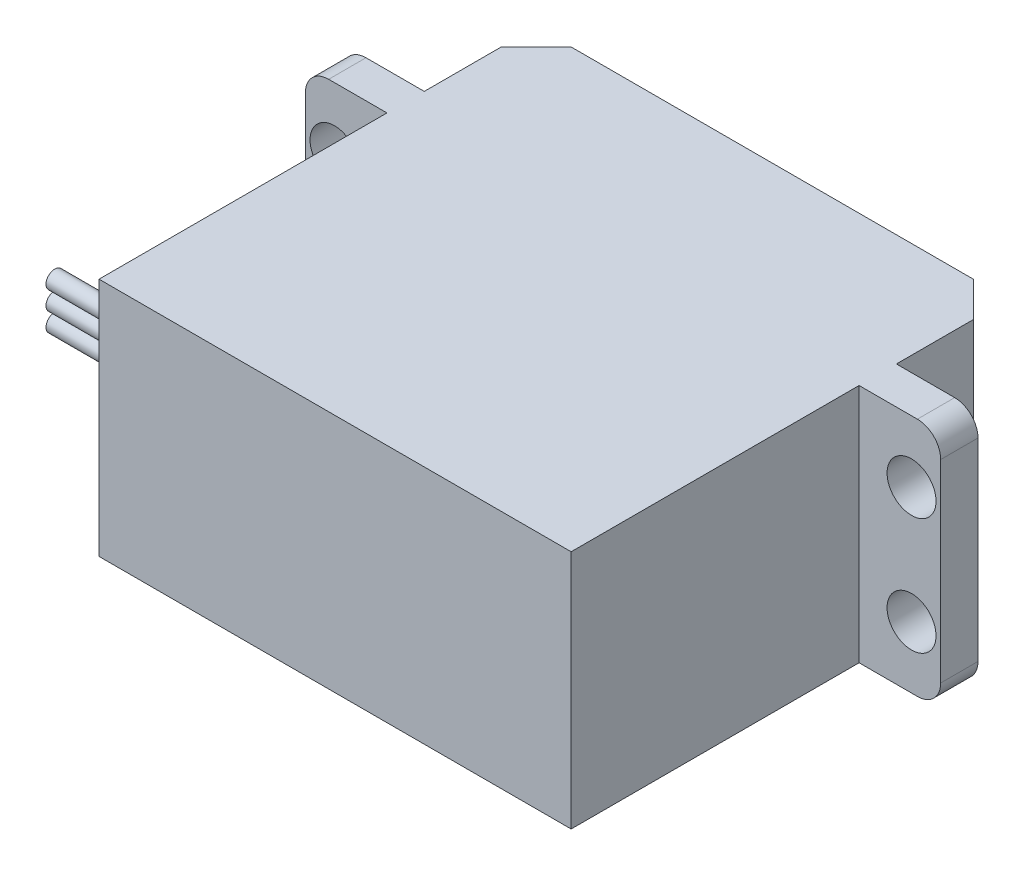
SolidWorks part; units mm, degrees
ref_plane "Plan de face" through (0, 0, 0) normal (0, 0, 1) x (1, 0, 0)
ref_plane "Plan de dessus" through (0, 0, 0) normal (0, 1, 0) x (1, 0, 0)
ref_plane "Plan de droite" through (0, 0, 0) normal (1, 0, 0) x (0, 0, -1)
sketch "Esquisse1" plane through (0, 0, 0) normal (0, 1, 0) x (1, 0, 0)
  line L0 (0, 0) -> (0, 9.3) construction
  line L5 (-17.25, 9.3) -> (17.25, 9.3)
  line L6 (17.25, 9.3) -> (20.25, 6.3)
  line L7 (20.25, 6.3) -> (20.25, -28.2)
  line L8 (20.25, -28.2) -> (-20.25, -28.2)
  line L9 (-20.25, 6.3) -> (-20.25, -28.2)
  line L10 (-17.25, 9.3) -> (-20.25, 6.3)
  point P9 (0, -28.2)
  dimension "D1" = 40.5
  dimension "D2" = 37.5
  dimension "D3" = 3
  dimension "D4" = 3
  dimension "D5" = 28.2
extrude "Boss.-Extru.1" add sketch "Esquisse1" along normal mid plane 20.6
ref_plane "Plan1" through (0, 0, 3.5) normal (0, 0, 1) x (1, 0, 0)
sketch "Esquisse3" plane through (0, 0, 3.5) normal (0, 0, 1) x (1, 0, 0)
  line L1 (0, 0) -> (20.25, 0) construction
  line L2 (20.25, 10.3) -> (20.25, -10.3) construction
  line L3 (0, 0) -> (0, 10.3) construction
  line L4 (17.25, 10.3) -> (-17.25, 10.3) construction
  line L16 (20.25, 10.3) -> (27.25, 10.3)
  line L17 (27.25, 10.3) -> (27.25, -10.3)
  line L18 (-20.25, 10.3) -> (-27.25, 10.3)
  line L19 (-27.25, 10.3) -> (-27.25, -10.3)
  line L20 (20.25, 10.3) -> (20.25, -10.3)
  line L21 (20.25, -10.3) -> (27.25, -10.3)
  line L22 (-20.25, -10.3) -> (-27.25, -10.3)
  line L23 (-20.25, 10.3) -> (-20.25, -10.3)
  circle A4 centre (24.75, 5) radius 2.1
  circle A5 centre (24.75, -5) radius 2.1
  circle A8 centre (-24.75, 5) radius 2.1
  circle A9 centre (-24.75, -5) radius 2.1
  point P25 (27.25, 0)
  dimension "D4" = 4.2
  dimension "D1" = 10
  dimension "D2" = 49.5
  dimension "D3" = 54.5
extrude "Boss.-Extru.2" add sketch "Esquisse3" against normal blind 3.2
sketch "Esquisse4" plane through (0, 0, 0) normal (0, 1, 0) x (1, 0, 0)
  line L0 (20.25, -0.3) -> (20.25, 1.6)
  line L1 (20.25, -0.3) -> (20.25, 6.3) construction
  line L3 (25.9, -0.3) -> (25.9, 0.2)
  line L4 (25.9, -0.3) -> (20.25, -0.3)
  line L5 (0, 0) -> (0, 11.6297) construction
  line L8 (-25.9, -0.3) -> (-20.25, -0.3)
  line L9 (27.25, -0.3) -> (20.25, -0.3) construction
  line L10 (25.9, 0.2) -> (21.65, 1.6)
  line L11 (21.65, 1.6) -> (20.25, 1.6)
  line L12 (-25.9, -0.3) -> (-25.9, 0.2)
  line L13 (-25.9, 0.2) -> (-21.65, 1.6)
  line L14 (-21.65, 1.6) -> (-20.25, 1.6)
  line L15 (-20.25, -0.3) -> (-20.25, 1.6)
  dimension "D1" = 51.8
  dimension "D2" = 1.9
  dimension "D3" = 1.4
  dimension "D4" = 0.5
extrude "Boss.-Extru.3" add sketch "Esquisse4" along normal mid plane 1.7
sketch "Esquisse8" plane through (0, 0, -9.3) normal (0, 0, -1) x (-1, 0, 0)
  line L0 (0, 0) -> (10, 0) construction
  line L2 (20.25, 10.3) -> (20.25, -10.3) construction
  circle A0 centre (10, 0) radius 6.75
  dimension "D1" = 13.5
  dimension "D2" = 10.25
extrude "Boss.-Extru.7" add sketch "Esquisse8" along normal blind 1
sketch "Esquisse5" plane through (0, 0, -10.3) normal (0, 0, -1) x (-1, 0, 0)
  line L0 (0, 0) -> (10, 0) construction
  circle A0 centre (10, 0) radius 2.925
  dimension "D1" = 5.85
extrude "Boss.-Extru.4" add sketch "Esquisse5" along normal blind 4.3
fillet "Congé1" radius 2 4 edges at (-27.25, 10.3, 1.9) (-27.25, -10.3, 1.9) (27.25, 10.3, 1.9) (27.25, -10.3, 1.9)
sketch "Esquisse6" plane through (-20.25, 0, 0) normal (-1, 0, 0) x (0, 0, 1)
  line L0 (19.9, 0) -> (0, 0) construction
  line L1 (19.9, 3.4) -> (22.9, 3.4)
  line L2 (19.9, 3.4) -> (19.9, -3.4)
  line L3 (19.9, -3.4) -> (22.9, -3.4)
  line L4 (22.9, 3.4) -> (22.9, -3.4)
  line L5 (28.2, 10.3) -> (28.2, -10.3) construction
  point P7 (21.4, -3.4)
  dimension "D1" = 6.8
  dimension "D2" = 3
  dimension "D3" = 6.8
extrude "Boss.-Extru.5" add sketch "Esquisse6" along normal blind 5.3
sketch "Esquisse7" plane through (-25.55, 0, 0) normal (-1, 0, 0) x (0, 0, 1)
  line L0 (21.4, 3.4) -> (21.4, -3.4) construction
  line L1 (22.9, 3.4) -> (19.9, 3.4) construction
  line L2 (19.9, -3.4) -> (22.9, -3.4) construction
  line L3 (21.4, 0) -> (22.9, 0) construction
  line L4 (22.9, -3.4) -> (22.9, 3.4) construction
  circle A0 centre (21.4, 0) radius 0.75
  circle A1 centre (21.4, 1.6) radius 0.75
  circle A2 centre (21.4, -1.6) radius 0.75
  dimension "D1" = 1.5
  dimension "D2" = 1.6
extrude "Boss.-Extru.6" add sketch "Esquisse7" along normal blind 5.3
hole_wizard "Diamètre du perçage Ø3.0 (3)1" positions "Esquisse10" profile "Esquisse12" hole size "Ø3.0" standard "DIN"
sketch "Esquisse10" plane through (0, 0, -14.6) normal (0, 0, -1) x (-1, 0, 0)
  point P0 (10, 0)
sketch "Esquisse12" plane through (-10, 0, -14.6) normal (1, 0, 0) x (0, 1, 0)
  line L0 (0, 0) -> (0, 6.9013)
  line L1 (0, 6.9013) -> (1.5, 6)
  line L2 (1.5, 6) -> (1.5, 0)
  line L5 (1.5, 0) -> (0, 0)
  line L10 (0, 6.9013) -> (-1.5, 6) construction
  line L11 (0, -6.35) -> (0, 107.95) construction
  dimension "Diamètre du perçage" = 3
  dimension "Profondeur du perçage" = 6
  dimension "Angle de pointe" = 118
